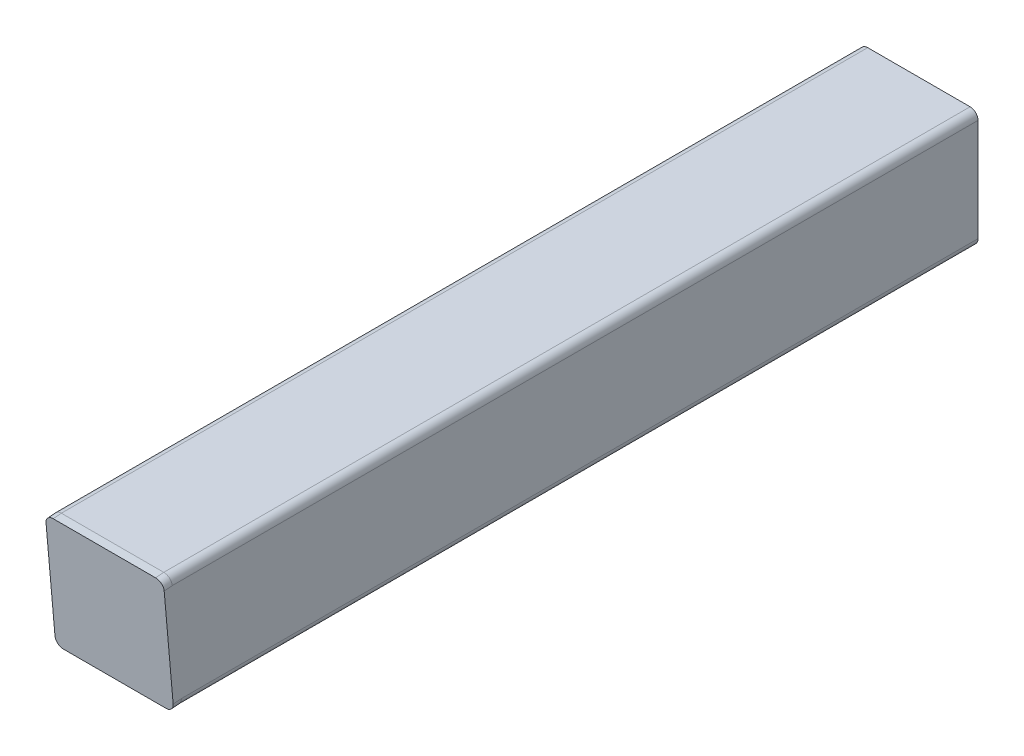
SolidWorks part; units mm, degrees
material "ASTM A500 Grade B Steel"
ref_plane "Front Plane" through (0, 0, 0) normal (0, 0, 1) x (1, 0, 0)
ref_plane "Top Plane" through (0, 0, 0) normal (0, 1, 0) x (1, 0, 0)
ref_plane "Right Plane" through (0, 0, 0) normal (1, 0, 0) x (0, 0, -1)
sketch "Sketch1" plane through (0, 0, 0) normal (0, 0, 1) x (1, 0, 0)
  line L0 (5.3086, -2.7686) -> (32.7914, -2.7686)
  line L1 (2.54, 0) -> (35.56, 0)
  line L2 (0, -2.54) -> (0, -35.56)
  line L3 (2.54, -38.1) -> (35.56, -38.1)
  line L4 (38.1, -2.54) -> (38.1, -35.56)
  line L5 (35.3314, -5.3086) -> (35.3314, -32.7914)
  line L6 (5.3086, -35.3314) -> (32.7914, -35.3314)
  line L7 (2.7686, -5.3086) -> (2.7686, -32.7914)
  line L8 (0, 0) -> (0, -38.1) construction
  line L9 (0, -38.1) -> (38.1, -38.1) construction
  line L10 (38.1, 0) -> (38.1, -38.1) construction
  line L11 (2.7686, -2.7686) -> (2.7686, -35.3314) construction
  line L12 (2.7686, -35.3314) -> (35.3314, -35.3314) construction
  line L13 (35.3314, -2.7686) -> (35.3314, -35.3314) construction
  line L14 (2.7686, -2.7686) -> (35.3314, -2.7686) construction
  line L15 (0, 0) -> (38.1, 0) construction
  arc A0 (0, -35.56) -> (2.54, -38.1) centre (2.54, -35.56) ccw
  arc A1 (38.1, -35.56) -> (35.56, -38.1) centre (35.56, -35.56) cw
  arc A2 (2.7686, -32.7914) -> (5.3086, -35.3314) centre (5.3086, -32.7914) ccw
  arc A3 (32.7914, -35.3314) -> (35.3314, -32.7914) centre (32.7914, -32.7914) ccw
  arc A4 (35.3314, -5.3086) -> (32.7914, -2.7686) centre (32.7914, -5.3086) ccw
  arc A5 (38.1, -2.54) -> (35.56, 0) centre (35.56, -2.54) ccw
  arc A6 (0, -2.54) -> (2.54, 0) centre (2.54, -2.54) cw
  arc A7 (5.3086, -2.7686) -> (2.7686, -5.3086) centre (5.3086, -5.3086) ccw
  point P12 (0, -38.1)
  dimension "D4" = 2.54
  dimension "D3" = 2.7686
extrude "Boss-Extrude1" add sketch "Sketch1" along normal blind 260
sketch "Sketch2" plane through (38.1, 0, 0) normal (1, 0, 0) x (0, 0, -1)
  line L0 (-260, 0) -> (-256.6667, -38.1)
  line L1 (-260, -38.1) -> (0, -38.1) construction
  line L5 (-260, 0) -> (-260, -38.1)
  line L6 (-256.6667, -38.1) -> (-260, -38.1)
  dimension "D1" = 5
extrude "Cut-Extrude1" cut sketch "Sketch2" against normal through all
sketch "Sketch3" plane through (0, -22.5743, 258.025) normal (0, -0.0872, 0.9962) x (1, 0, 0)
  line L4 (2.54, -15.585) -> (35.56, -15.585)
  line L5 (38.1, -13.0353) -> (38.1, 20.1108)
  line L6 (35.56, 22.6605) -> (2.54, 22.6605)
  line L7 (0, 20.1108) -> (0, -13.0353)
  line L8 (2.54, -15.585) -> (35.56, -15.585)
  line L9 (38.1, -13.0353) -> (38.1, 20.1108)
  line L10 (35.56, 22.6605) -> (2.54, 22.6605)
  line L11 (0, 20.1108) -> (0, -13.0353)
  ellipse E4 centre (35.56, -13.0353) end of major axis (35.56, -15.585) minor radius 2.54 (35.56, -15.585) -> (38.1, -13.0353) ccw
  ellipse E5 centre (35.56, 20.1108) end of major axis (35.56, 17.5611) minor radius 2.54 (38.1, 20.1108) -> (35.56, 22.6605) ccw
  ellipse E6 centre (2.54, 20.1108) end of major axis (2.54, 17.5611) minor radius 2.54 (2.54, 22.6605) -> (0, 20.1108) ccw
  ellipse E7 centre (2.54, -13.0353) end of major axis (2.54, -15.585) minor radius 2.54 (0, -13.0353) -> (2.54, -15.585) ccw
  ellipse E8 centre (35.56, -13.0353) end of major axis (35.56, -15.585) minor radius 2.54 (35.56, -15.585) -> (38.1, -13.0353) ccw
  ellipse E9 centre (35.56, 20.1108) end of major axis (35.56, 17.5611) minor radius 2.54 (38.1, 20.1108) -> (35.56, 22.6605) ccw
  ellipse E10 centre (2.54, 20.1108) end of major axis (2.54, 17.5611) minor radius 2.54 (2.54, 22.6605) -> (0, 20.1108) ccw
  ellipse E11 centre (2.54, -13.0353) end of major axis (2.54, -15.585) minor radius 2.54 (0, -13.0353) -> (2.54, -15.585) ccw
  dimension "D1" = 0
extrude "Boss-Extrude2" add sketch "Sketch3" along normal up to surface (2.6244 mm away)
